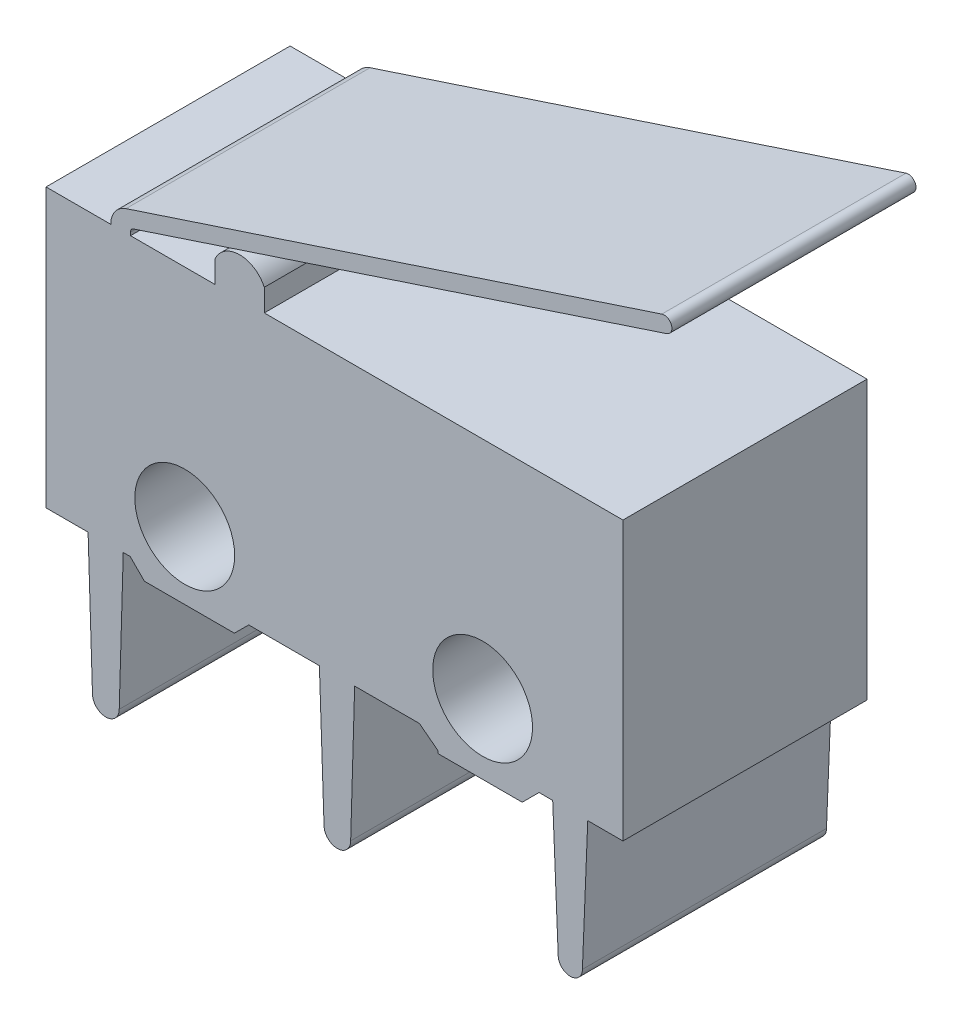
SolidWorks part; units mm, degrees
ref_plane "Ön Düzlem" through (0, 0, 0) normal (0, 0, 1) x (1, 0, 0)
ref_plane "Üst Düzlem" through (0, 0, 0) normal (0, 1, 0) x (1, 0, 0)
ref_plane "Sağ Düzlem" through (0, 0, 0) normal (1, 0, 0) x (0, 0, -1)
sketch "Çizim1" plane through (0, 0, 0) normal (0, 0, 1) x (1, 0, 0)
  line L0 (14.6222, 11.7809) -> (27.9001, 11.7809) construction
  line L1 (-0.7375, -36.0785) -> (0.2102, -36.0785)
  line L2 (-0.7375, -29.8151) -> (0.7211, -29.8151)
  line L3 (-0.7375, -29.8151) -> (-0.7375, -36.0785)
  line L5 (12.2625, -29.8151) -> (12.2625, -36.0785)
  line L6 (1.158, -36.0785) -> (1.4807, -36.4012)
  line L7 (1.4807, -36.4012) -> (3.5072, -36.4012)
  line L8 (3.5072, -36.4012) -> (3.8299, -36.0785)
  line L9 (3.8299, -36.0785) -> (5.4225, -36.0785)
  line L10 (7.6763, -36.0785) -> (8.0976, -36.4012)
  line L11 (8.0976, -36.4012) -> (8.0976, -36.4574)
  line L12 (8.0976, -36.4574) -> (9.9929, -36.4574)
  line L13 (9.9929, -36.4574) -> (10.3718, -36.0785)
  line L14 (10.3718, -36.0785) -> (10.6796, -36.0785)
  line L15 (0.2102, -36.0785) -> (0.309, -39.1849)
  line L17 (1.0026, -36.0785) -> (0.9118, -39.1849)
  line L18 (5.4225, -36.0785) -> (5.5269, -39.1439)
  line L20 (6.127, -39.1439) -> (6.2166, -36.0785)
  line L21 (10.6796, -36.0785) -> (10.8037, -39.0412)
  line L23 (11.3487, -39.0412) -> (11.4696, -36.0785)
  line L24 (1.0026, -36.0785) -> (1.158, -36.0785)
  line L25 (6.2166, -36.0785) -> (7.6763, -36.0785)
  line L26 (11.4696, -36.0785) -> (12.2625, -36.0785)
  line L27 (3.0693, -29.8151) -> (3.0693, -29.3151)
  line L28 (0.7211, -29.8151) -> (0.7211, -29.8125)
  line L29 (4.1803, -29.3151) -> (4.1803, -29.8151)
  line L30 (4.1803, -29.8151) -> (12.2625, -29.8151)
  line L31 (1.0646, -29.3376) -> (13.1389, -25.3582)
  line L33 (13.247, -25.686) -> (1.2346, -29.6497)
  line L34 (1.1659, -29.7447) -> (1.1659, -29.8151)
  line L35 (1.1659, -29.8151) -> (3.0693, -29.8151)
  arc A0 (0.309, -39.1849) -> (0.9118, -39.1849) centre (0.6104, -39.1849) ccw
  arc A1 (5.5269, -39.1439) -> (6.127, -39.1439) centre (5.827, -39.1439) ccw
  arc A2 (10.8037, -39.0412) -> (11.3487, -39.0412) centre (11.0762, -39.0412) ccw
  circle A3 centre (2.3876, -34.8833) radius 1.125
  circle A4 centre (9.1002, -34.8833) radius 1.125
  arc A5 (3.0693, -29.3151) -> (4.1803, -29.3151) centre (3.6248, -29.5664) cw
  arc A6 (13.1389, -25.3582) -> (13.247, -25.686) centre (13.193, -25.5221) cw
  arc A7 (0.7211, -29.8125) -> (1.0646, -29.3376) centre (1.2211, -29.8125) cw
  arc A8 (1.2346, -29.6497) -> (1.1659, -29.7447) centre (1.2659, -29.7447) ccw
  point P46 (1.1659, -29.6724)
  point P47 (0.7211, -29.4508)
  dimension "D3" = 2.25
  dimension "D4" = 2.25
  dimension "D5" = 0.5
  dimension "D6" = 0.1
  dimension "D1" = 13
  dimension "D2" = 0.79
  dimension "D7" = 0.5
extrude "Yükseklik-Ekstrüzyon1" add sketch "Çizim1" along normal blind 5.5
